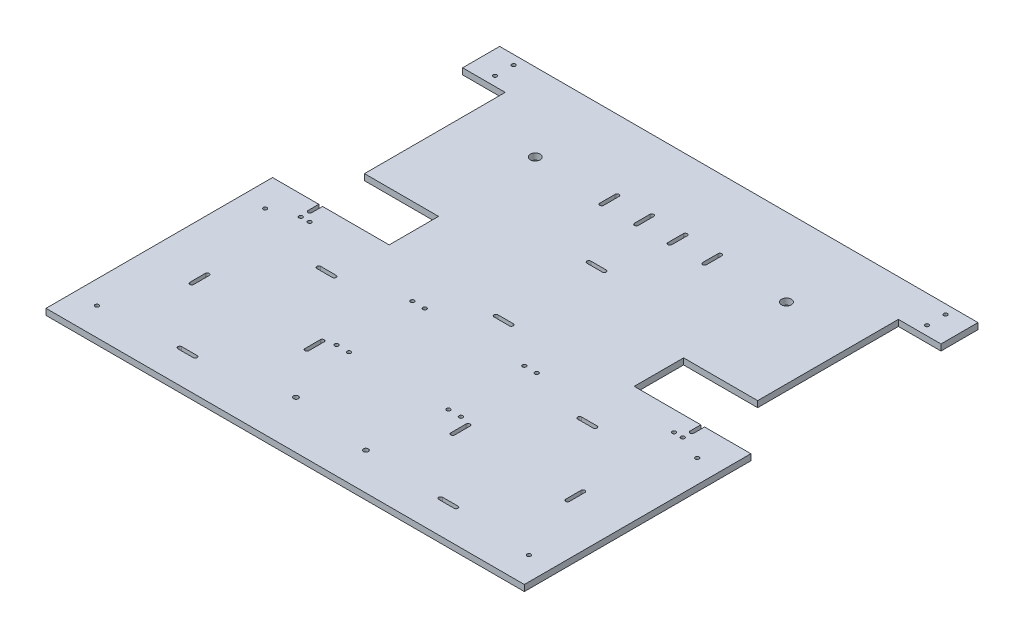
SolidWorks part; units mm, degrees
material "Beech"
ref_plane "Front Plane" through (0, 0, 0) normal (0, 0, 1) x (1, 0, 0)
ref_plane "Top Plane" through (0, 0, 0) normal (0, 1, 0) x (1, 0, 0)
ref_plane "Right Plane" through (0, 0, 0) normal (1, 0, 0) x (0, 0, -1)
sketch "Sketch1" plane through (0, 0, 0) normal (0, 1, 0) x (1, 0, 0)
  line L0 (-387.5, -367.5) -> (387.5, -367.5)
  line L1 (-387.5, -367.5) -> (-387.5, 367.5)
  line L2 (387.5, -367.5) -> (387.5, 367.5)
  line L3 (-387.5, 367.5) -> (387.5, 367.5)
  line L4 (-387.5, -367.5) -> (387.5, 367.5) construction
  line L5 (387.5, -367.5) -> (-387.5, 367.5) construction
  point P1 (0, 0)
  dimension "D1" = 775
  dimension "D2" = 735
extrude "Boss-Extrude1" add sketch "Sketch1" along normal blind 10
sketch "Sketch2" plane through (0, 10, 0) normal (0, 1, 0) x (1, 0, 0)
  line L0 (387.5, 307.5) -> (318.5, 307.5)
  line L1 (387.5, -367.5) -> (387.5, 367.5) construction
  line L2 (318.5, 307.5) -> (318.5, 79.5)
  line L3 (318.5, 79.5) -> (198.5, 79.5)
  line L4 (198.5, 79.5) -> (198.5, -0.5)
  line L5 (198.5, -0.5) -> (387.5, -0.5)
  line L6 (387.5, -0.5) -> (387.5, 307.5)
  line L7 (387.5, 367.5) -> (-387.5, 367.5) construction
  line L8 (0, 0) -> (0, 191.9909) construction
  line L9 (-387.5, -0.5) -> (-387.5, 307.5)
  line L10 (-198.5, -0.5) -> (-387.5, -0.5)
  line L11 (-198.5, 79.5) -> (-198.5, -0.5)
  line L12 (-318.5, 79.5) -> (-198.5, 79.5)
  line L13 (-318.5, 307.5) -> (-318.5, 79.5)
  line L14 (-387.5, 307.5) -> (-318.5, 307.5)
  line L15 (-198.5, 39.5) -> (-387.5, 39.5) construction
  line L16 (198.5, 39.5) -> (387.5, 39.5) construction
  line L17 (-387.5, 367.5) -> (-387.5, -367.5) construction
  dimension "D1" = 69
  dimension "D2" = 60
  dimension "D3" = 80
  dimension "D4" = 120
  dimension "D5" = 328
extrude "Cut-Extrude1" cut sketch "Sketch2" against normal blind 10
sketch "Sketch3" plane through (0, 10, 0) normal (0, 1, 0) x (1, 0, 0)
  line L0 (-91.2755, 0) -> (0, 0) construction
  line L1 (0, 0) -> (0, 91.7612) construction
  line L2 (-387.5, 322.5) -> (-312.5, 322.5) construction
  line L3 (-387.5, 307.5) -> (-387.5, 322.5) construction
  line L4 (-350, -322.5) -> (-350, 322.5) construction
  line L5 (-318.5, 307.5) -> (-387.5, 307.5) construction
  line L6 (-387.5, 367.5) -> (-387.5, 307.5) construction
  line L7 (-387.5, 322.5) -> (-387.5, 352.5) construction
  line L8 (-387.5, 352.5) -> (-387.5, 367.5) construction
  line L10 (-312.5, 352.5) -> (-387.5, 352.5) construction
  circle A0 centre (-350, 322.5) radius 3.05
  circle A1 centre (350, 322.5) radius 3.05
  circle A2 centre (350, -322.5) radius 3.05
  circle A3 centre (-350, -322.5) radius 3.05
  circle A4 centre (-350, 0) radius 3.05 construction
  circle A5 centre (350, -50) radius 3.05
  circle A6 centre (-350, -50) radius 3.05
  circle A7 centre (-350, 352.5) radius 3.05
  circle A8 centre (350, 352.5) radius 3.05
  dimension "D1" = 6.1
  dimension "D2" = 75
  dimension "D3" = 50
  dimension "D4" = 15
extrude "Cut-Extrude2" cut sketch "Sketch3" against normal blind 10
sketch "Sketch4" plane through (0, 10, 0) normal (0, 1, 0) x (1, 0, 0)
  line L0 (-304.4, -214.3) -> (-304.4, -189.3) construction
  line L1 (-223.8, -89.2) -> (-198.8, -89.2) construction
  line L2 (-304.4, -201.8) -> (-118.2, -201.8) construction
  line L3 (-118.2, -189.3) -> (-118.2, -214.3) construction
  line L4 (-301.3, -214.3) -> (-301.3, -189.3)
  line L5 (-198.8, -314.4) -> (-223.8, -314.4) construction
  line L6 (-211.3, -89.2) -> (-211.3, -314.4) construction
  line L7 (-223.8, -92.3) -> (-198.8, -92.3)
  line L8 (-121.3, -189.3) -> (-121.3, -214.3)
  line L9 (-198.8, -311.3) -> (-223.8, -311.3)
  line L10 (-307.5, -214.3) -> (-307.5, -189.3)
  line L11 (-223.8, -86.1) -> (-198.8, -86.1)
  line L12 (-115.1, -189.3) -> (-115.1, -214.3)
  line L13 (-198.8, -317.5) -> (-223.8, -317.5)
  line L14 (0, 0) -> (0, -100.3819) construction
  line L15 (211.3, -89.2) -> (211.3, -314.4) construction
  line L16 (198.8, -314.4) -> (223.8, -314.4) construction
  line L17 (118.2, -189.3) -> (118.2, -214.3) construction
  line L18 (304.4, -201.8) -> (118.2, -201.8) construction
  line L19 (223.8, -89.2) -> (198.8, -89.2) construction
  line L20 (304.4, -214.3) -> (304.4, -189.3) construction
  line L21 (198.8, -317.5) -> (223.8, -317.5)
  line L22 (115.1, -189.3) -> (115.1, -214.3)
  line L23 (223.8, -86.1) -> (198.8, -86.1)
  line L24 (307.5, -214.3) -> (307.5, -189.3)
  line L25 (198.8, -311.3) -> (223.8, -311.3)
  line L26 (121.3, -189.3) -> (121.3, -214.3)
  line L27 (223.8, -92.3) -> (198.8, -92.3)
  line L28 (301.3, -214.3) -> (301.3, -189.3)
  line L29 (-387.5, -0.5) -> (-387.5, -367.5) construction
  line L30 (-387.5, -367.5) -> (387.5, -367.5) construction
  arc A0 (-301.3, -214.3) -> (-307.5, -214.3) centre (-304.4, -214.3) cw
  arc A1 (-301.3, -189.3) -> (-307.5, -189.3) centre (-304.4, -189.3) ccw
  arc A2 (-223.8, -92.3) -> (-223.8, -86.1) centre (-223.8, -89.2) cw
  arc A3 (-198.8, -92.3) -> (-198.8, -86.1) centre (-198.8, -89.2) ccw
  arc A4 (-121.3, -189.3) -> (-115.1, -189.3) centre (-118.2, -189.3) cw
  arc A5 (-121.3, -214.3) -> (-115.1, -214.3) centre (-118.2, -214.3) ccw
  arc A6 (-198.8, -311.3) -> (-198.8, -317.5) centre (-198.8, -314.4) cw
  arc A7 (-223.8, -311.3) -> (-223.8, -317.5) centre (-223.8, -314.4) ccw
  arc A8 (223.8, -311.3) -> (223.8, -317.5) centre (223.8, -314.4) cw
  arc A9 (198.8, -311.3) -> (198.8, -317.5) centre (198.8, -314.4) ccw
  arc A10 (121.3, -214.3) -> (115.1, -214.3) centre (118.2, -214.3) cw
  arc A11 (121.3, -189.3) -> (115.1, -189.3) centre (118.2, -189.3) ccw
  arc A12 (198.8, -92.3) -> (198.8, -86.1) centre (198.8, -89.2) cw
  arc A13 (223.8, -92.3) -> (223.8, -86.1) centre (223.8, -89.2) ccw
  arc A14 (301.3, -189.3) -> (307.5, -189.3) centre (304.4, -189.3) cw
  arc A15 (301.3, -214.3) -> (307.5, -214.3) centre (304.4, -214.3) ccw
  point P10 (-211.3, -201.8)
  point P56 (211.3, -201.8)
  dimension "D1" = 25
  dimension "D4" = 180
  dimension "D5" = 219
  dimension "D6" = 80
  dimension "D7" = 50
  dimension "D2" = 3.1
  dimension "D3" = 3.1
extrude "Cut-Extrude3" cut sketch "Sketch4" against normal blind 10
sketch "Sketch5" plane through (0, 10, 0) normal (0, 1, 0) x (1, 0, 0)
  circle A0 centre (70.7428, -307.5) radius 4
  circle A1 centre (-60.166, -290) radius 4
  dimension "D1" = 8
extrude "Cut-Extrude4" cut sketch "Sketch5" against normal blind 10
sketch "Sketch6" plane through (0, 10, 0) normal (0, 1, 0) x (1, 0, 0)
  line L0 (-80.6366, -60.7152) -> (-80.6033, -183.5228) construction
  line L1 (-80.6366, -60.7152) -> (-100.7629, -60.7207) construction
  line L2 (-80.6033, -183.5228) -> (-100.7295, -183.5283) construction
  line L3 (-100.7629, -60.7207) -> (-100.7295, -183.5283) construction
  line L4 (-80.6366, -60.7152) -> (-100.7295, -183.5283) construction
  line L5 (-80.6033, -183.5228) -> (-100.7629, -60.7207) construction
  line L6 (0, 0) -> (0, -89.3933) construction
  line L7 (80.6033, -183.5228) -> (100.7629, -60.7207) construction
  line L8 (80.6366, -60.7152) -> (100.7295, -183.5283) construction
  line L9 (100.7629, -60.7207) -> (100.7295, -183.5283) construction
  line L10 (80.6033, -183.5228) -> (100.7295, -183.5283) construction
  line L11 (80.6366, -60.7152) -> (100.7629, -60.7207) construction
  line L12 (80.6366, -60.7152) -> (80.6033, -183.5228) construction
  line L13 (-295.2137, -32.749) -> (-309.45, -32.749) construction
  line L14 (-309.45, -17.9748) -> (-309.45, -0.5) construction
  line L15 (-387.5, -0.5) -> (-198.5, -0.5) construction
  line L16 (-312.5, -17.9748) -> (-312.5, -0.5)
  line L17 (-306.4, -17.9748) -> (-306.4, -0.5)
  line L18 (-387.5, -0.5) -> (-387.5, -367.5) construction
  line L19 (309.45, -17.9748) -> (309.45, -0.5) construction
  line L20 (312.5, -17.9748) -> (312.5, -0.5)
  line L21 (306.4, -17.9748) -> (306.4, -0.5)
  circle A0 centre (-100.7295, -183.5283) radius 3.05
  circle A1 centre (-80.6033, -183.5228) radius 3.05
  circle A2 centre (-100.7629, -60.7207) radius 3.05
  circle A3 centre (-80.6366, -60.7152) radius 3.05
  circle A4 centre (-350, -50) radius 3.05 construction
  circle A5 centre (80.6366, -60.7152) radius 3.05
  circle A6 centre (100.7629, -60.7207) radius 3.05
  circle A7 centre (80.6033, -183.5228) radius 3.05
  circle A8 centre (100.7295, -183.5283) radius 3.05
  circle A9 centre (-309.45, -32.749) radius 3.05
  circle A10 centre (-295.2137, -32.749) radius 3.05
  circle A11 centre (309.45, -32.749) radius 3.05
  circle A12 centre (295.2137, -32.749) radius 3.05
  arc A13 (-312.5, -17.9748) -> (-306.4, -17.9748) centre (-309.45, -17.9748) ccw
  arc A14 (-306.4, -0.5) -> (-312.5, -0.5) centre (-309.45, -0.5) ccw
  arc A15 (312.5, -17.9748) -> (306.4, -17.9748) centre (309.45, -17.9748) cw
  arc A16 (306.4, -0.5) -> (312.5, -0.5) centre (309.45, -0.5) cw
  point P9 (-90.6831, -122.1218)
  point P22 (90.6831, -122.1218)
  point P35 (-309.45, -9.2374)
  point P44 (309.45, -9.2374)
  dimension "D1" = 75
extrude "Cut-Extrude5" cut sketch "Sketch6" against normal blind 10
sketch "Sketch7" plane through (0, 10, 0) normal (0, 1, 0) x (1, 0, 0)
  line L0 (0, 0) -> (0, -13.6025) construction
  line L1 (-12.5, -13.6025) -> (12.5, -13.6025) construction
  line L2 (-12.5, -10.5025) -> (12.5, -10.5025)
  line L3 (-12.5, -16.7025) -> (12.5, -16.7025)
  line L4 (-12.5, 137.0768) -> (12.5, 137.0768) construction
  line L5 (-12.5, 140.1768) -> (12.5, 140.1768)
  line L6 (-12.5, 133.9768) -> (12.5, 133.9768)
  line L7 (-27.1162, 253.6146) -> (-27.1162, 228.6146) construction
  line L8 (-24.0162, 253.6146) -> (-24.0162, 228.6146)
  line L9 (-30.2162, 253.6146) -> (-30.2162, 228.6146)
  line L10 (-83.3162, 253.6146) -> (-83.3162, 228.6146) construction
  line L11 (-80.2162, 253.6146) -> (-80.2162, 228.6146)
  line L12 (-86.4162, 253.6146) -> (-86.4162, 228.6146)
  line L13 (-198.8, -86.1) -> (-223.8, -86.1) construction
  line L14 (-203.4944, 241.1146) -> (-83.3162, 241.1146) construction
  line L15 (-83.3162, 241.1146) -> (-27.1162, 241.1146) construction
  line L16 (83.3162, 253.6146) -> (83.3162, 228.6146) construction
  line L17 (80.2162, 253.6146) -> (80.2162, 228.6146)
  line L18 (86.4162, 253.6146) -> (86.4162, 228.6146)
  line L19 (27.1162, 253.6146) -> (27.1162, 228.6146) construction
  line L20 (24.0162, 253.6146) -> (24.0162, 228.6146)
  line L21 (30.2162, 253.6146) -> (30.2162, 228.6146)
  arc A0 (-12.5, -10.5025) -> (-12.5, -16.7025) centre (-12.5, -13.6025) ccw
  circle A1 centre (-203.4944, 241.1146) radius 8
  arc A2 (12.5, -16.7025) -> (12.5, -10.5025) centre (12.5, -13.6025) ccw
  arc A3 (-12.5, 140.1768) -> (-12.5, 133.9768) centre (-12.5, 137.0768) ccw
  arc A4 (12.5, 133.9768) -> (12.5, 140.1768) centre (12.5, 137.0768) ccw
  arc A5 (-24.0162, 253.6146) -> (-30.2162, 253.6146) centre (-27.1162, 253.6146) ccw
  arc A6 (-30.2162, 228.6146) -> (-24.0162, 228.6146) centre (-27.1162, 228.6146) ccw
  arc A7 (-80.2162, 253.6146) -> (-86.4162, 253.6146) centre (-83.3162, 253.6146) ccw
  arc A8 (-86.4162, 228.6146) -> (-80.2162, 228.6146) centre (-83.3162, 228.6146) ccw
  arc A9 (-198.8, -92.3) -> (-198.8, -86.1) centre (-198.8, -89.2) ccw construction
  arc A10 (80.2162, 253.6146) -> (86.4162, 253.6146) centre (83.3162, 253.6146) cw
  arc A11 (86.4162, 228.6146) -> (80.2162, 228.6146) centre (83.3162, 228.6146) cw
  arc A12 (24.0162, 253.6146) -> (30.2162, 253.6146) centre (27.1162, 253.6146) cw
  arc A13 (30.2162, 228.6146) -> (24.0162, 228.6146) centre (27.1162, 228.6146) cw
  circle A14 centre (203.4944, 241.1146) radius 8
  point P7 (0, -13.6025)
  point P13 (0, 137.0768)
  point P20 (-27.1162, 241.1146)
  point P27 (-83.3162, 241.1146)
  point P42 (83.3162, 241.1146)
  point P49 (27.1162, 241.1146)
  dimension "D1" = 16
  dimension "D2" = 50
extrude "Cut-Extrude6" cut sketch "Sketch7" against normal blind 10
